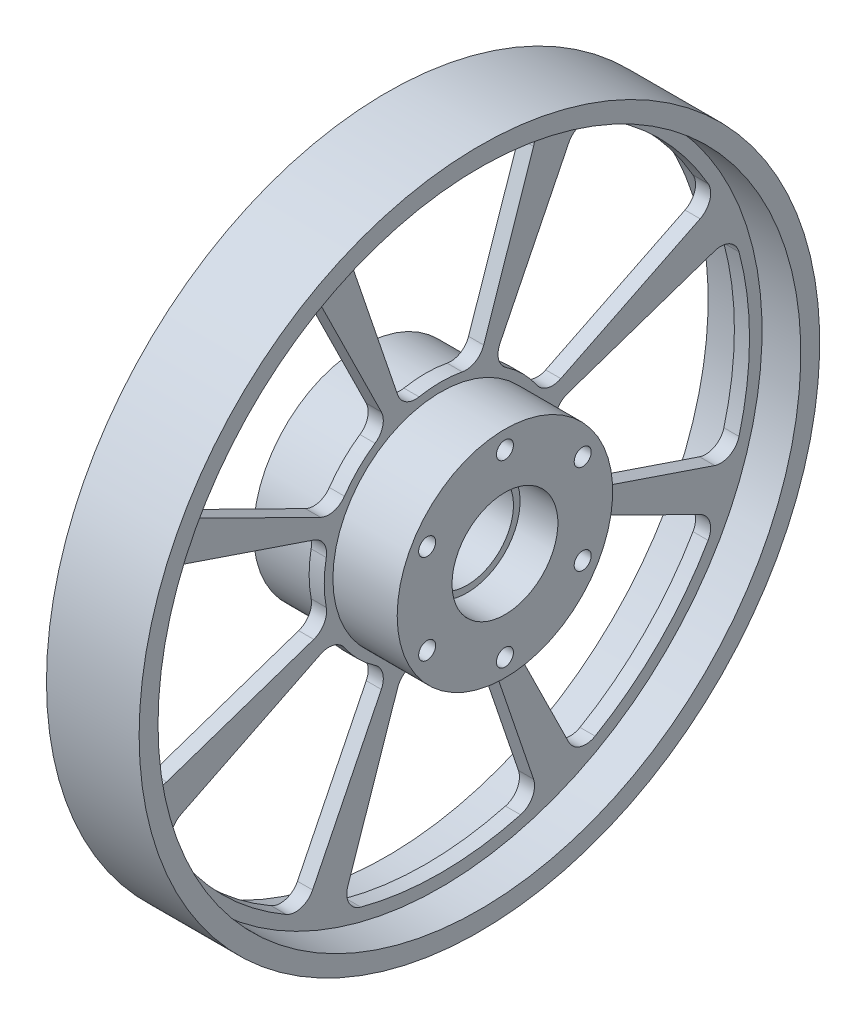
SolidWorks part; units mm, degrees
ref_plane "Front Plane" through (0, 0, 0) normal (0, 0, 1) x (1, 0, 0)
ref_plane "Top Plane" through (0, 0, 0) normal (0, 1, 0) x (1, 0, 0)
ref_plane "Right Plane" through (0, 0, 0) normal (1, 0, 0) x (0, 0, -1)
sketch "Sketch1" plane through (0, 0, 0) normal (0, 1, 0) x (1, 0, 0)
  line L0 (0, 0) -> (0, 12.25) construction
  line L1 (-9, 12.25) -> (9, 12.25)
  line L2 (9, 12.25) -> (9, 14)
  line L3 (9, 14) -> (19, 14)
  line L4 (19, 14) -> (19, 28.5)
  line L5 (19, 28.5) -> (2, 28.5)
  line L6 (0, 0) -> (21.3342, 0) construction
  line L7 (2, 28.5) -> (2, 85)
  line L8 (2, 85) -> (12.25, 85)
  line L9 (12.25, 85) -> (12.25, 90)
  line L10 (12.25, 90) -> (-12.25, 90)
  line L11 (-9, 12.25) -> (-9, 14)
  line L12 (-9, 14) -> (-19, 14)
  line L13 (-19, 14) -> (-19, 28.5)
  line L14 (-19, 28.5) -> (-2, 28.5)
  line L15 (-2, 28.5) -> (-2, 85)
  line L16 (-2, 85) -> (-12.25, 85)
  line L17 (-12.25, 85) -> (-12.25, 90)
  point P21 (0, 90)
  dimension "D1" = 12.25
  dimension "D2" = 1.75
  dimension "D3" = 14.5
  dimension "D4" = 9
  dimension "D5" = 10
  dimension "D6" = 17
  dimension "D7" = 56.5
  dimension "D8" = 5
  dimension "D9" = 10.25
revolve "Revolve1" add sketch "Sketch1" angle 360 about L6
sketch "Sketch2" plane through (19, 0, 0) normal (1, 0, 0) x (0, 0, -1)
  line L0 (0, 0) -> (0, 23.75) construction
  circle A0 centre (0, 23.75) radius 2.25
  circle A1 centre (20.5681, 11.875) radius 2.25
  circle A2 centre (20.5681, -11.875) radius 2.25
  circle A3 centre (0, -23.75) radius 2.25
  circle A4 centre (-20.5681, -11.875) radius 2.25
  circle A5 centre (-20.5681, 11.875) radius 2.25
  point P17 (0, 0)
  dimension "D1" = 4.5
  dimension "D2" = 23.75
  dimension "D3" = 6
extrude "Cut-Extrude1" cut sketch "Sketch2" against normal blind 40
sketch "Sketch3" plane through (-2, 0, 0) normal (-1, 0, 0) x (0, 0, 1)
  line L0 (33.8646, 68.6186) -> (15.6829, 31.7776)
  line L1 (68.6186, 33.8646) -> (31.7776, 15.6829)
  line L2 (72.4666, 24.5748) -> (33.5596, 11.3807)
  line L3 (-24.5748, 72.4666) -> (-11.3807, 33.5596)
  line L4 (24.5748, 72.4666) -> (11.3807, 33.5596)
  line L5 (72.4666, -24.5748) -> (33.5596, -11.3807)
  line L6 (68.6186, -33.8646) -> (31.7776, -15.6829)
  line L7 (33.8646, -68.6186) -> (15.6829, -31.7776)
  line L8 (24.5748, -72.4666) -> (11.3807, -33.5596)
  line L9 (-24.5748, -72.4666) -> (-11.3807, -33.5596)
  line L10 (-33.8646, -68.6186) -> (-15.6829, -31.7776)
  line L11 (-68.6186, -33.8646) -> (-31.7776, -15.6829)
  line L12 (-72.4666, -24.5748) -> (-33.5596, -11.3807)
  line L13 (-72.4666, 24.5748) -> (-33.5596, 11.3807)
  line L14 (-68.6186, 33.8646) -> (-31.7776, 15.6829)
  line L15 (-33.8646, 68.6186) -> (-15.6829, 31.7776)
  arc A0 (-21.1333, 78.9021) -> (21.1333, 78.9021) centre (0, 0) cw
  arc A1 (-5.7171, 30.2523) -> (5.7171, 30.2523) centre (0, 0) cw
  arc A2 (-11.3807, 33.5596) -> (-5.7171, 30.2523) centre (-6.6456, 35.1654) ccw
  arc A3 (5.7171, 30.2523) -> (11.3807, 33.5596) centre (6.6456, 35.1654) ccw
  arc A4 (24.5748, 72.4666) -> (21.1333, 78.9021) centre (19.8396, 74.0724) ccw
  arc A5 (-21.1333, 78.9021) -> (-24.5748, 72.4666) centre (-19.8396, 74.0724) ccw
  arc A6 (40.8487, 70.7357) -> (33.8646, 68.6186) centre (38.3483, 66.4058) ccw
  arc A7 (17.349, 25.4342) -> (25.4342, 17.349) centre (0, 0) cw
  arc A8 (15.6829, 31.7776) -> (17.349, 25.4342) centre (20.1666, 29.5648) ccw
  arc A9 (25.4342, 17.349) -> (31.7776, 15.6829) centre (29.5648, 20.1666) ccw
  arc A10 (68.6186, 33.8646) -> (70.7357, 40.8487) centre (66.4058, 38.3483) ccw
  arc A11 (40.8487, 70.7357) -> (70.7357, 40.8487) centre (0, 0) cw
  arc A12 (78.9021, 21.1333) -> (72.4666, 24.5748) centre (74.0724, 19.8396) ccw
  arc A13 (30.2523, 5.7171) -> (30.2523, -5.7171) centre (0, 0) cw
  arc A14 (33.5596, 11.3807) -> (30.2523, 5.7171) centre (35.1654, 6.6456) ccw
  arc A15 (30.2523, -5.7171) -> (33.5596, -11.3807) centre (35.1654, -6.6456) ccw
  arc A16 (72.4666, -24.5748) -> (78.9021, -21.1333) centre (74.0724, -19.8396) ccw
  arc A17 (78.9021, 21.1333) -> (78.9021, -21.1333) centre (0, 0) cw
  arc A18 (70.7357, -40.8487) -> (68.6186, -33.8646) centre (66.4058, -38.3483) ccw
  arc A19 (25.4342, -17.349) -> (17.349, -25.4342) centre (0, 0) cw
  arc A20 (31.7776, -15.6829) -> (25.4342, -17.349) centre (29.5648, -20.1666) ccw
  arc A21 (17.349, -25.4342) -> (15.6829, -31.7776) centre (20.1666, -29.5648) ccw
  arc A22 (33.8646, -68.6186) -> (40.8487, -70.7357) centre (38.3483, -66.4058) ccw
  arc A23 (70.7357, -40.8487) -> (40.8487, -70.7357) centre (0, 0) cw
  arc A24 (21.1333, -78.9021) -> (24.5748, -72.4666) centre (19.8396, -74.0724) ccw
  arc A25 (5.7171, -30.2523) -> (-5.7171, -30.2523) centre (0, 0) cw
  arc A26 (11.3807, -33.5596) -> (5.7171, -30.2523) centre (6.6456, -35.1654) ccw
  arc A27 (-5.7171, -30.2523) -> (-11.3807, -33.5596) centre (-6.6456, -35.1654) ccw
  arc A28 (-24.5748, -72.4666) -> (-21.1333, -78.9021) centre (-19.8396, -74.0724) ccw
  arc A29 (21.1333, -78.9021) -> (-21.1333, -78.9021) centre (0, 0) cw
  arc A30 (-40.8487, -70.7357) -> (-33.8646, -68.6186) centre (-38.3483, -66.4058) ccw
  arc A31 (-17.349, -25.4342) -> (-25.4342, -17.349) centre (0, 0) cw
  arc A32 (-15.6829, -31.7776) -> (-17.349, -25.4342) centre (-20.1666, -29.5648) ccw
  arc A33 (-25.4342, -17.349) -> (-31.7776, -15.6829) centre (-29.5648, -20.1666) ccw
  arc A34 (-68.6186, -33.8646) -> (-70.7357, -40.8487) centre (-66.4058, -38.3483) ccw
  arc A35 (-40.8487, -70.7357) -> (-70.7357, -40.8487) centre (0, 0) cw
  arc A36 (-78.9021, -21.1333) -> (-72.4666, -24.5748) centre (-74.0724, -19.8396) ccw
  arc A37 (-30.2523, -5.7171) -> (-30.2523, 5.7171) centre (0, 0) cw
  arc A38 (-33.5596, -11.3807) -> (-30.2523, -5.7171) centre (-35.1654, -6.6456) ccw
  arc A39 (-30.2523, 5.7171) -> (-33.5596, 11.3807) centre (-35.1654, 6.6456) ccw
  arc A40 (-72.4666, 24.5748) -> (-78.9021, 21.1333) centre (-74.0724, 19.8396) ccw
  arc A41 (-78.9021, -21.1333) -> (-78.9021, 21.1333) centre (0, 0) cw
  arc A42 (-70.7357, 40.8487) -> (-68.6186, 33.8646) centre (-66.4058, 38.3483) ccw
  arc A43 (-25.4342, 17.349) -> (-17.349, 25.4342) centre (0, 0) cw
  arc A44 (-31.7776, 15.6829) -> (-25.4342, 17.349) centre (-29.5648, 20.1666) ccw
  arc A45 (-17.349, 25.4342) -> (-15.6829, 31.7776) centre (-20.1666, 29.5648) ccw
  arc A46 (-33.8646, 68.6186) -> (-40.8487, 70.7357) centre (-38.3483, 66.4058) ccw
  arc A47 (-70.7357, 40.8487) -> (-40.8487, 70.7357) centre (0, 0) cw
  point P100 (0, 0)
  dimension "D1" = 5
  dimension "D2" = 8
extrude "Cut-Extrude2" cut sketch "Sketch3" against normal blind 40
